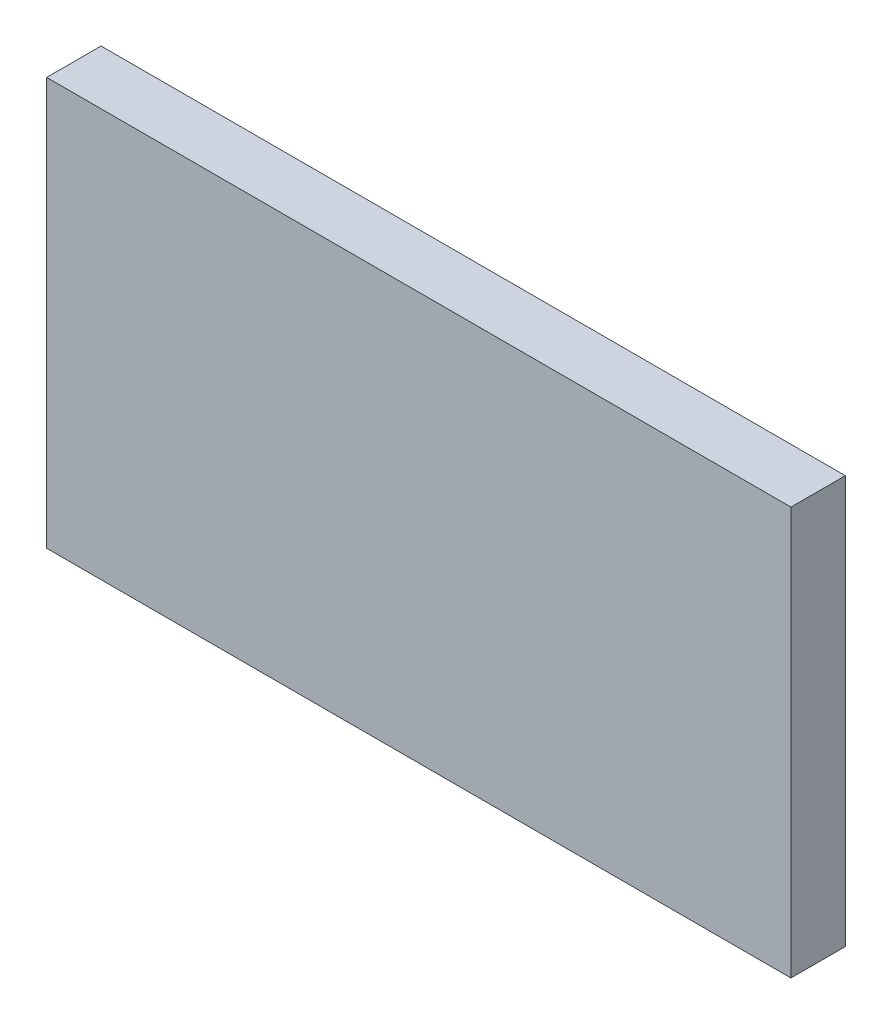
SolidWorks part; units mm, degrees
ref_plane "Front Plane" through (0, 0, 0) normal (0, 0, 1) x (1, 0, 0)
ref_plane "Top Plane" through (0, 0, 0) normal (0, 1, 0) x (1, 0, 0)
ref_plane "Right Plane" through (0, 0, 0) normal (1, 0, 0) x (0, 0, -1)
sketch "CurveSketch" plane through (0, 0, 0) normal (0, 0, 1) x (1, 0, 0)
  line L0 (-20.0525, -1.8635) -> (11.6665, -1.8635)
  line L1 (11.6665, -1.8635) -> (11.6665, 15.5175)
  line L2 (11.6665, 15.5175) -> (-20.0525, 15.5175)
  line L3 (-20.0525, 15.5175) -> (-20.0525, -1.8635)
extrude "CurveBoss" add sketch "CurveSketch" against normal blind 2.317
